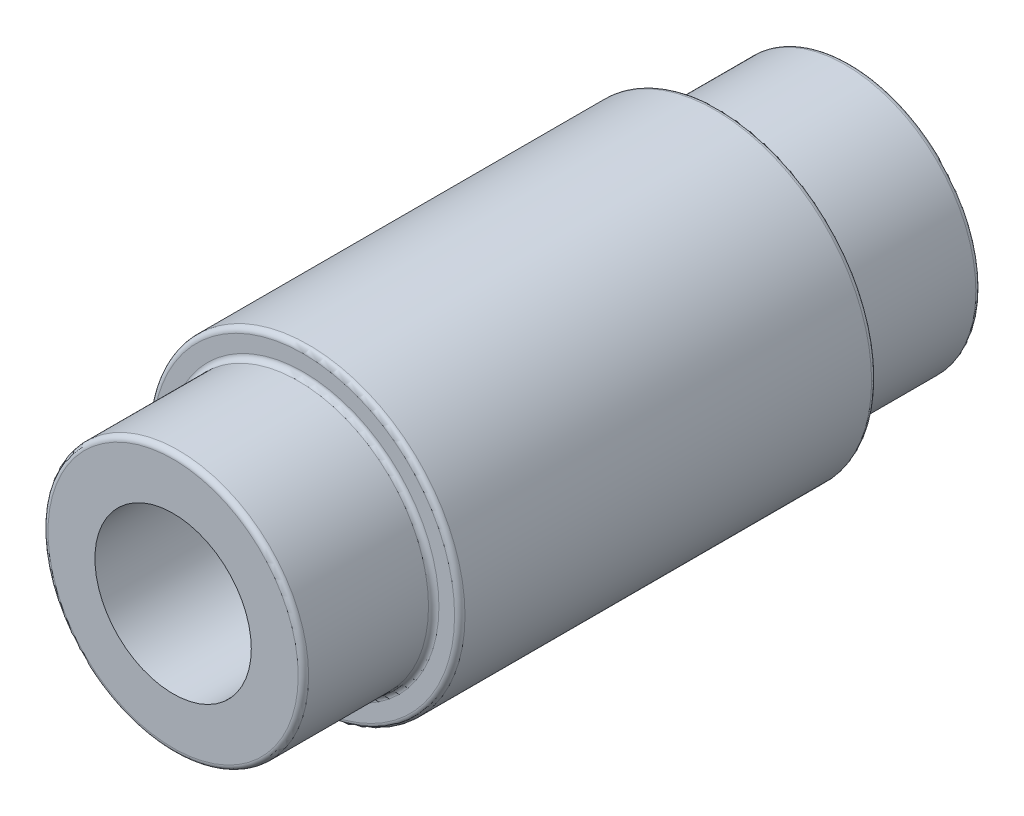
SolidWorks part; units mm, degrees
ref_plane "Front Plane" through (0, 0, 0) normal (0, 0, 1) x (1, 0, 0)
ref_plane "Top Plane" through (0, 0, 0) normal (0, 1, 0) x (1, 0, 0)
ref_plane "Right Plane" through (0, 0, 0) normal (1, 0, 0) x (0, 0, -1)
sketch "Sketch1" plane through (0, 0, 0) normal (0, 0, 1) x (1, 0, 0)
  circle A0 centre (0, 0) radius 0.3
  dimension "D1" = 0.6
extrude "Boss-Extrude1" add sketch "Sketch1" along normal mid plane 0.8
sketch "Sketch4" plane through (0, 0, 0) normal (0, 0, 1) x (1, 0, 0)
  circle A0 centre (0, 0) radius 0.25
  dimension "D1" = 0.5
extrude "Boss-Extrude3" add sketch "Sketch4" along normal mid plane 1.3
sketch "Sketch5" plane through (0, 0, 0.65) normal (0, 0, 1) x (1, 0, 0)
  circle A0 centre (0, 0) radius 0.15
  dimension "D1" = 0.3
extrude "Cut-Extrude1" cut sketch "Sketch5" against normal through all
fillet "Fillet1" radius 0.01 4 edges at (0.3, 0, -0.4) (0.3, 0, 0.4) (0.25, 0, -0.65) (0.25, 0, 0.65)
fillet "Fillet2" radius 0.01 2 edges at (0.25, 0, -0.4) (0.25, 0, 0.4)
